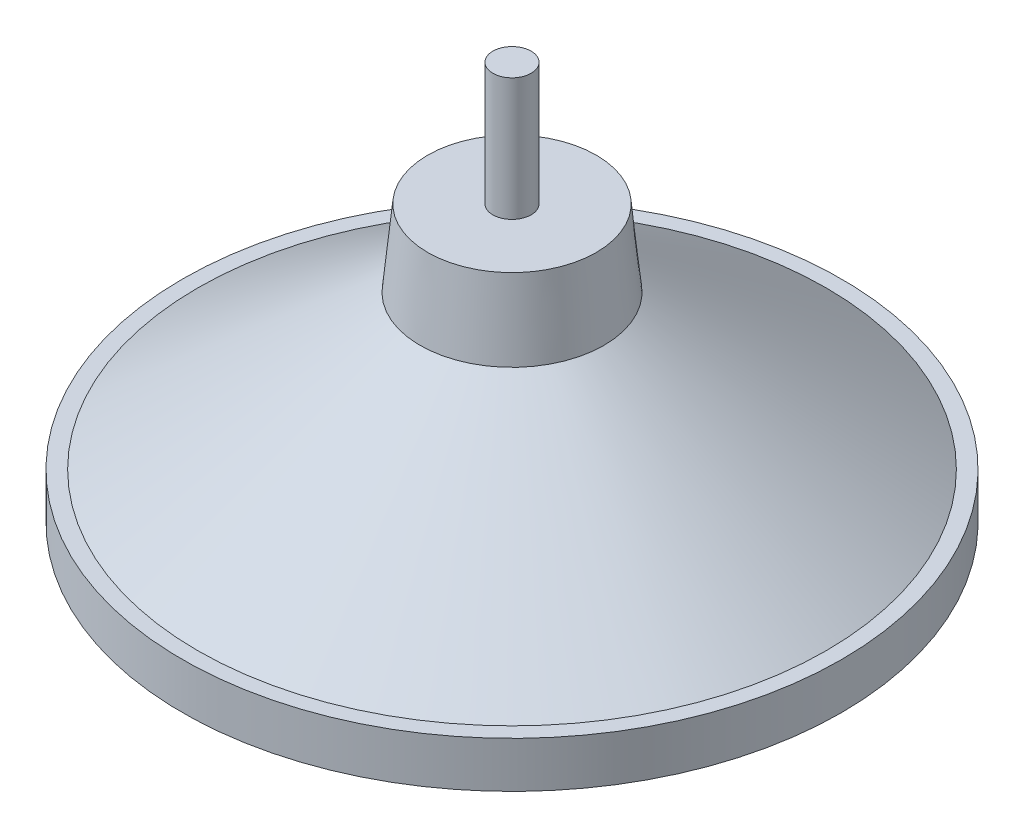
SolidWorks part; units mm, degrees
ref_plane "Front Plane" through (0, 0, 0) normal (0, 0, 1) x (1, 0, 0)
ref_plane "Top Plane" through (0, 0, 0) normal (0, 1, 0) x (1, 0, 0)
ref_plane "Right Plane" through (0, 0, 0) normal (1, 0, 0) x (0, 0, -1)
sketch "Sketch1" plane through (0, 0, 0) normal (0, 0, 1) x (1, 0, 0)
  line L0 (0, 0) -> (68.2625, 0)
  line L1 (68.2625, 0) -> (68.2625, 9.525)
  line L2 (68.2625, 9.525) -> (65.0875, 9.525)
  line L3 (65.0875, 9.525) -> (19.05, 41.275)
  line L4 (19.05, 41.275) -> (17.4625, 57.15)
  line L5 (17.4625, 57.15) -> (3.9687, 57.15)
  line L6 (0, 57.15) -> (0, 0)
  line L7 (3.9687, 57.15) -> (3.9687, 82.55)
  line L8 (3.9687, 82.55) -> (0, 82.55)
  line L9 (0, 82.55) -> (0, 57.15)
  dimension "D1" = 17.4625
  dimension "D2" = 68.2625
  dimension "D3" = 9.525
  dimension "D4" = 3.175
  dimension "D5" = 19.05
  dimension "D6" = 15.875
  dimension "D7" = 57.15
  dimension "D8" = 25.4
  dimension "D9" = 3.9688
revolve "Revolve1" add sketch "Sketch1" angle 360 about L6
